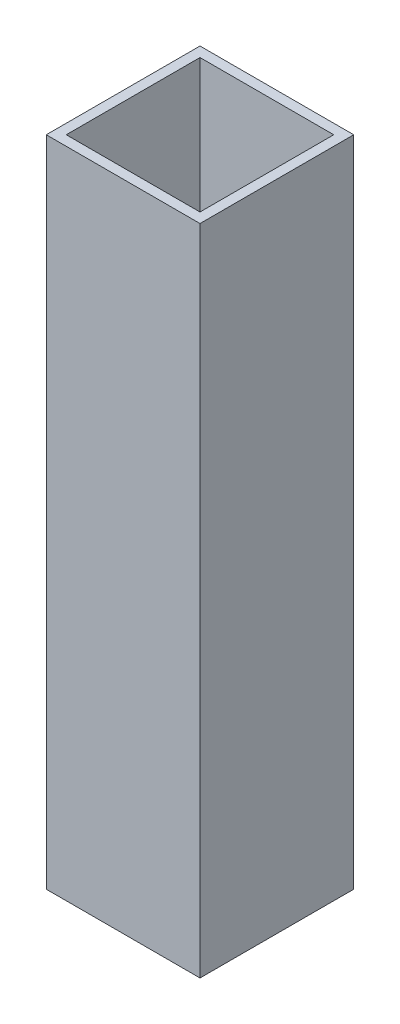
SolidWorks part; units mm, degrees
material "6061 Alloy"
ref_plane "Front Plane" through (0, 0, 0) normal (0, 0, 1) x (1, 0, 0)
ref_plane "Top Plane" through (0, 0, 0) normal (0, 1, 0) x (1, 0, 0)
ref_plane "Right Plane" through (0, 0, 0) normal (1, 0, 0) x (0, 0, -1)
sketch "Sketch1" plane through (0, 0, 0) normal (0, 1, 0) x (1, 0, 0)
  line L1 (0, 0) -> (25.4, 0)
  line L2 (0, 0) -> (0, -25.4)
  line L3 (0, -25.4) -> (25.4, -25.4)
  line L4 (25.4, 0) -> (25.4, -25.4)
extrude "Boss-Extrude1" add sketch "Sketch1" along normal blind 107.95
sketch "Sketch2" plane through (0, 107.95, 0) normal (0, 1, 0) x (1, 0, 0)
  line L0 (0, 0) -> (0, -25.4) construction
  line L1 (1.651, -1.651) -> (23.749, -1.651)
  line L2 (1.651, -1.651) -> (1.651, -23.749)
  line L3 (1.651, -23.749) -> (23.749, -23.749)
  line L4 (23.749, -1.651) -> (23.749, -23.749)
  line L5 (25.4, 0) -> (0, 0) construction
  line L6 (25.4, -25.4) -> (25.4, 0) construction
  line L7 (0, -25.4) -> (25.4, -25.4) construction
  dimension "D1" = 1.651
  dimension "D2" = 1.651
  dimension "D3" = 1.651
  dimension "D4" = 1.651
extrude "Cut-Extrude1" cut sketch "Sketch2" against normal blind 76.2
